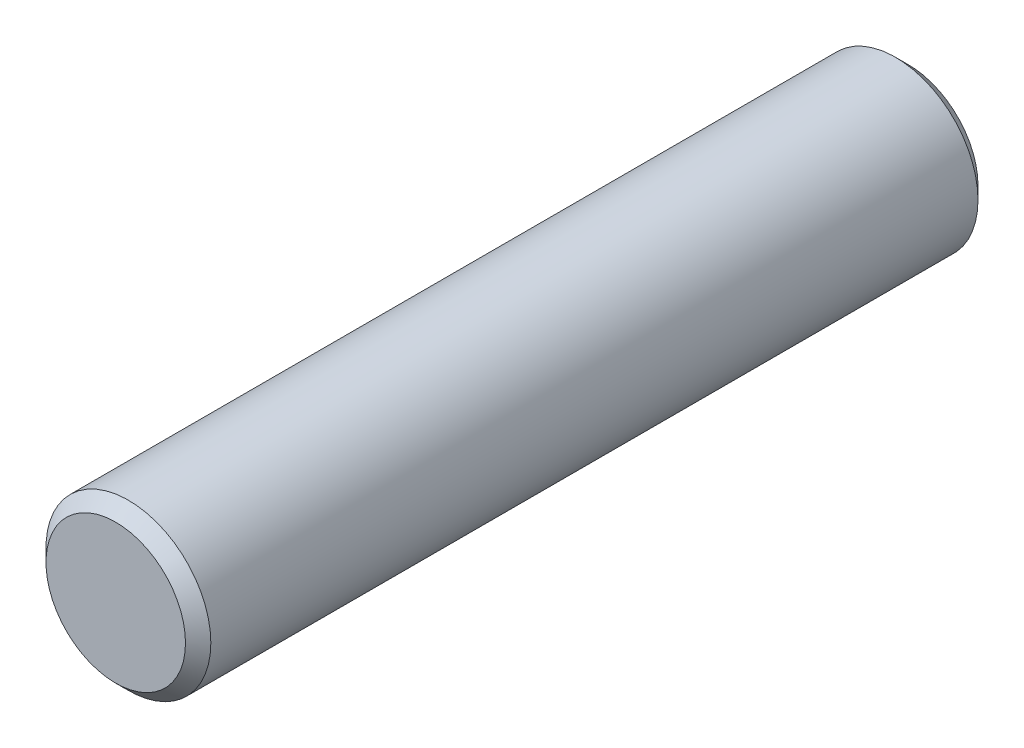
SolidWorks part; units mm, degrees
material "Plain Carbon Steel"
ref_plane "Front Plane" through (0, 0, 0) normal (0, 0, 1) x (1, 0, 0)
ref_plane "Top Plane" through (0, 0, 0) normal (0, 1, 0) x (1, 0, 0)
ref_plane "Right Plane" through (0, 0, 0) normal (1, 0, 0) x (0, 0, -1)
sketch "Sketch1" plane through (0, 0, 0) normal (0, 0, 1) x (1, 0, 0)
  circle A0 centre (0, 0) radius 1.651
  dimension "D1" = 3.302
extrude "Boss-Extrude1" add sketch "Sketch1" along normal blind 15.875
chamfer "Chamfer1" distance 0.254 angle 45 2 edges at (1.651, 0, 0) (1.651, 0, 15.875)
